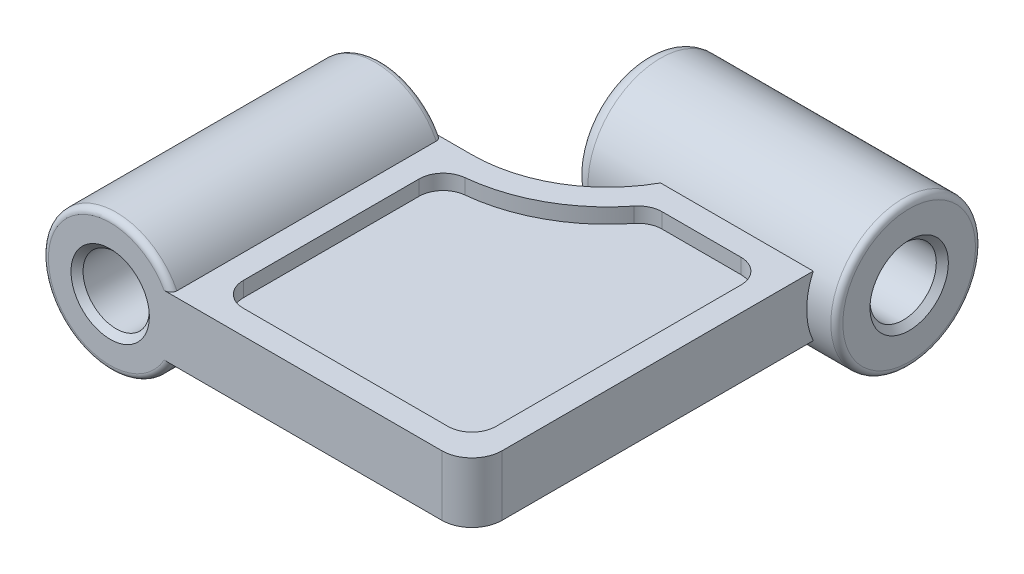
SolidWorks part; units mm, degrees
material "1060 Alloy"
ref_plane "Front Plane" through (0, 0, 0) normal (0, 0, 1) x (1, 0, 0)
ref_plane "Top Plane" through (0, 0, 0) normal (0, 1, 0) x (1, 0, 0)
ref_plane "Right Plane" through (0, 0, 0) normal (1, 0, 0) x (0, 0, -1)
sketch "Sketch1" plane through (0, 0, 0) normal (0, 1, 0) x (1, 0, 0)
  line L0 (0, -45) -> (-45, -45)
  line L1 (90, -135) -> (-45, -135)
  line L2 (90, -135) -> (90, 0)
  line L3 (90, 0) -> (-45, 0)
  line L4 (-45, -135) -> (-45, 0)
  circle A0 centre (0, 0) radius 45
  dimension "D1" = 90
  dimension "D2" = 90
  dimension "D3" = 135
  dimension "D4" = 135
extrude "Boss-Extrude1" add sketch "Sketch1" along normal mid plane 20 contours A0 L4 L1 L2 L3
sketch "Sketch2" plane through (0, 0, 135) normal (0, 0, 1) x (1, 0, 0)
  circle A0 centre (-30, 0) radius 22.5
  point P2 (0, 0)
  dimension "D1" = 45
  dimension "D2" = 30
extrude "Boss-Extrude2" add sketch "Sketch2" against normal blind 90
sketch "Sketch3" plane through (0, 0, 135) normal (0, 0, 1) x (1, 0, 0)
  circle A0 centre (-30, 0) radius 11
  dimension "D1" = 22
extrude "Cut-Extrude1" cut sketch "Sketch3" against normal through all
sketch "Sketch4" plane through (90, 0, 0) normal (1, 0, 0) x (0, 0, -1)
  circle A0 centre (0, 0) radius 24
  point P2 (0, 0)
  dimension "D1" = 48
extrude "Boss-Extrude3" add sketch "Sketch4" against normal blind 87.5 from offset 10
sketch "Sketch5" plane through (100, 0, 0) normal (1, 0, 0) x (0, 0, -1)
  circle A0 centre (0, 0) radius 11
  dimension "D1" = 22
extrude "Cut-Extrude2" cut sketch "Sketch5" against normal through all
sketch "Sketch6" plane through (0, 10, 0) normal (0, 1, 0) x (1, 0, 0)
  line L10 (82, -29.8174) -> (43.8169, -29.8174)
  line L11 (0, -53) -> (-1.8444, -53)
  line L12 (-1.8444, -53) -> (-1.8444, -127)
  line L13 (-1.8444, -127) -> (82, -127)
  line L14 (82, -127) -> (82, -29.8174)
  line L15 (74, -29.8174) -> (47.8627, -29.8174)
  line L17 (-1.8444, -60.6886) -> (-1.8444, -119)
  line L18 (6.1556, -127) -> (74, -127)
  line L19 (82, -119) -> (82, -37.8174)
  arc A1 (82, -119) -> (74, -127) centre (74, -119) cw
  arc A2 (0, -53) -> (43.8169, -29.8174) centre (0, 0) ccw
  arc A3 (5.3483, -52.7295) -> (41.5857, -32.8578) centre (0, 0) ccw
  arc A4 (6.1556, -127) -> (-1.8444, -119) centre (6.1556, -119) cw
  arc A5 (82, -37.8174) -> (74, -29.8174) centre (74, -37.8174) ccw
  arc A6 (47.8627, -29.8174) -> (41.5857, -32.8578) centre (47.8627, -37.8174) ccw
  arc A7 (-1.8444, -60.6886) -> (5.3483, -52.7295) centre (6.1556, -60.6886) cw
  dimension "D2" = 8
  dimension "D1" = 8
extrude "Cut-Extrude3" cut sketch "Sketch6" against normal blind 5
mirror "Mirror1" about plane through (0, 0, 0) normal (0, 1, 0) of "Cut-Extrude3"
fillet "Fillet1" radius 10 1 edges at (90, 0, 135)
fillet "Fillet2" radius 5 1 edges at (12.5, 0, -24)
fillet "Fillet3" radius 2 3 edges at (100, 0, -24) (-52.5, 0, 135) (-52.5, 0, 45)
chamfer "Chamfer1" distance 2 angle 45 4 edges at (100, 0, -11) (12.5, 0, -11) (-19, 0, 135) (-19, 0, 45)
equation "\"A\"= 90"
equation "\"B\" = 45"
equation "\"C\" = 135"
equation "\"D\"= 22"
equation "\"Y\"= \"C\" / 2 + 20"
equation "\"D1@Sketch1\"=\"A\""
equation "\"D2@Sketch1\"=\"A\""
equation "\"D3@Sketch1\"=\"C\""
equation "\"D4@Sketch1\"=\"C\""
equation "\"D1@Sketch2\"=\"B\""
equation "\"D1@Boss-Extrude2\"=\"A\""
equation "\"D1@Sketch3\"=\"D\""
equation "\"D1@Boss-Extrude3\"=\"Y\""
equation "\"D1@Sketch5\"=\"D\""
